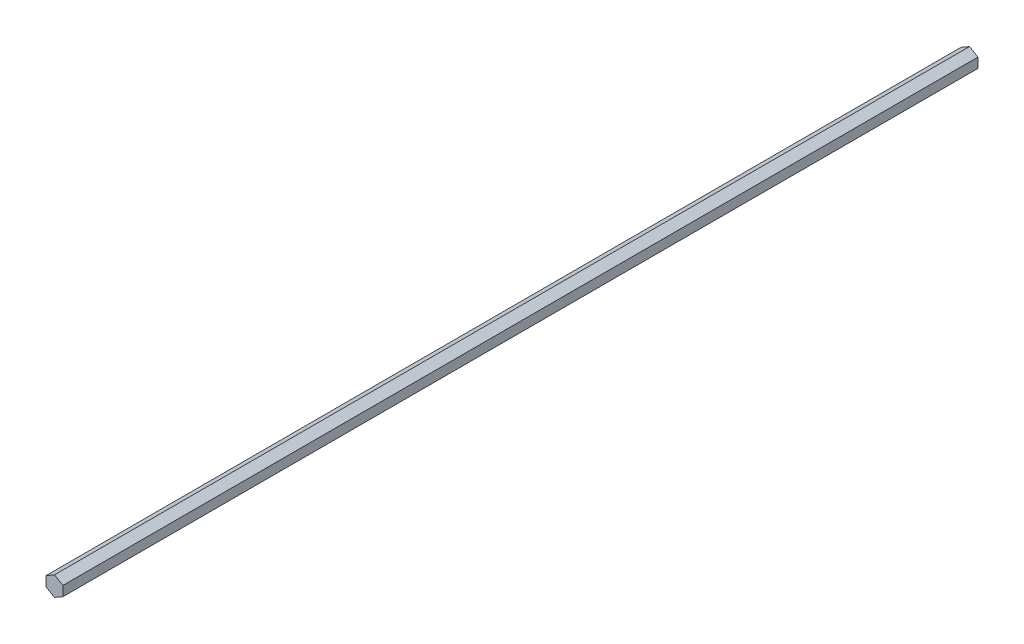
SolidWorks part; units mm, degrees
ref_plane "Front Plane" through (0, 0, 0) normal (0, 0, 1) x (1, 0, 0)
ref_plane "Top Plane" through (0, 0, 0) normal (0, 1, 0) x (1, 0, 0)
ref_plane "Right Plane" through (0, 0, 0) normal (1, 0, 0) x (0, 0, -1)
sketch "Sketch1" plane through (0, 0, 0) normal (0, 0, 1) x (1, 0, 0)
  line L1 (6.35, 3.6662) -> (0, 7.3323)
  line L2 (0, 7.3323) -> (-6.35, 3.6662)
  line L3 (-6.35, 3.6662) -> (-6.35, -3.6662)
  line L4 (-6.35, -3.6662) -> (0, -7.3323)
  line L5 (0, -7.3323) -> (6.35, -3.6662)
  line L6 (6.35, -3.6662) -> (6.35, 3.6662)
  circle A0 centre (0, 0) radius 6.35 construction
  dimension "D1" = 12.7
extrude "Boss-Extrude1" add sketch "Sketch1" along normal mid plane 685.8
